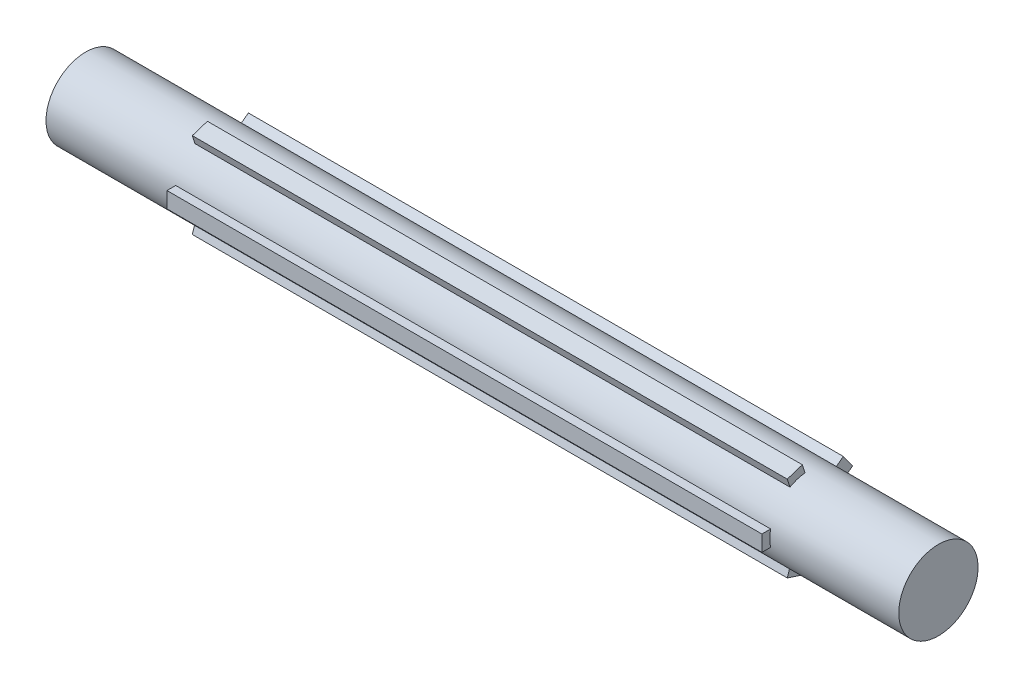
SolidWorks part; units mm, degrees
ref_plane "Front Plane" through (0, 0, 0) normal (0, 0, 1) x (1, 0, 0)
ref_plane "Top Plane" through (0, 0, 0) normal (0, 1, 0) x (1, 0, 0)
ref_plane "Right Plane" through (0, 0, 0) normal (1, 0, 0) x (0, 0, -1)
sketch "Sketch1" plane through (0, 0, 0) normal (0, 0, 1) x (1, 0, 0)
  line L0 (0, 0) -> (143786.2644, 0) construction
  line L1 (-107.5, 0) -> (107.5, 0)
  line L2 (-107.5, 10) -> (107.5, 10)
  line L3 (-107.5, 10) -> (-107.5, 0)
  line L4 (107.5, 10) -> (107.5, 0)
  point P6 (0, 0)
  dimension "D1" = 215
  dimension "D2" = 20
revolve "Revolve1" add sketch "Sketch1" angle 360 about L0
sketch "Sketch2" plane through (0, 0, 0) normal (1, 0, 0) x (0, 0, -1)
  line L1 (-12, -2) -> (-8, -2)
  line L2 (-12, -2) -> (-12, 2)
  line L3 (-12, 2) -> (-8, 2)
  line L4 (-8, -2) -> (-8, 2)
  line L5 (-12, -2) -> (-8, 2) construction
  line L6 (-12, 2) -> (-8, -2) construction
  circle A0 centre (0, 0) radius 10 construction
  point P0 (-10, 0)
  dimension "D1" = 4
  dimension "D2" = 4
extrude "Boss-Extrude1" add sketch "Sketch2" along normal mid plane 150
pattern_circular "CirPattern1" count 5 over 360 about axis through (0, 0, 0) along (1, 0, 0) of "Boss-Extrude1"
